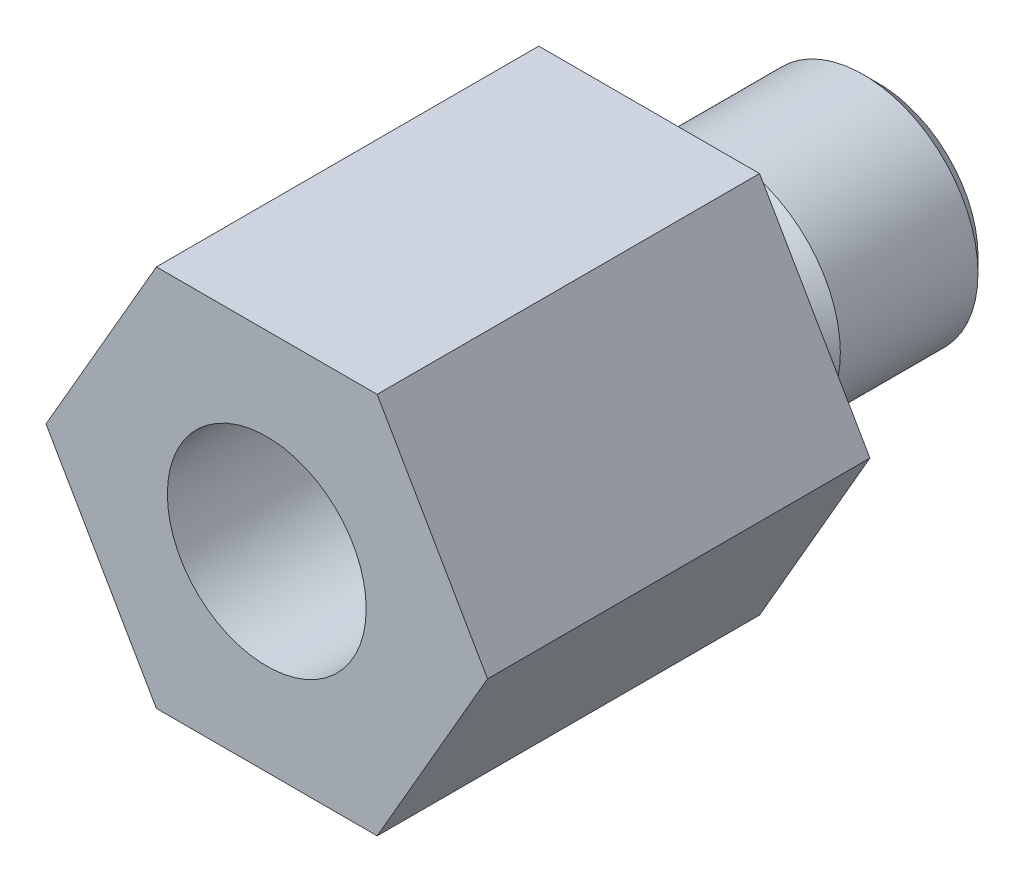
SolidWorks part; units mm, degrees
ref_plane "Plan de face" through (0, 0, 0) normal (0, 0, 1) x (1, 0, 0)
ref_plane "Plan de dessus" through (0, 0, 0) normal (0, 1, 0) x (1, 0, 0)
ref_plane "Plan de droite" through (0, 0, 0) normal (1, 0, 0) x (0, 0, -1)
sketch "Esquisse1" plane through (0, 0, 0) normal (0, 0, 1) x (1, 0, 0)
  line L1 (1.4434, 2.5) -> (-1.4434, 2.5)
  line L2 (-1.4434, 2.5) -> (-2.8868, 0)
  line L3 (-2.8868, 0) -> (-1.4434, -2.5)
  line L4 (-1.4434, -2.5) -> (1.4434, -2.5)
  line L5 (1.4434, -2.5) -> (2.8868, 0)
  line L6 (2.8868, 0) -> (1.4434, 2.5)
  circle A0 centre (0, 0) radius 2.5 construction
  dimension "D1" = 5
extrude "Extrusion1" add sketch "Esquisse1" along normal blind 5
sketch "Esquisse2" plane through (0, 0, 0) normal (0, 0, -1) x (-1, 0, 0)
  circle A0 centre (0, 0) radius 1.5
extrude "Extrusion2" add sketch "Esquisse2" along normal blind 3
cosmetic thread "Représentation de filetage1" parameters "D1"=3, "D2"=2.6
chamfer "Chanfrein1" distance 0.2 angle 45
sketch "Esquisse3" plane through (0, 0, 5) normal (0, 0, 1) x (1, 0, 0)
  circle A0 centre (0, 0) radius 1.3
extrude "Enlèv. mat.-Extru.1" cut sketch "Esquisse3" against normal blind 3
cosmetic thread "Représentation de filetage2" parameters "D1"=3, "D2"=3
sketch "Esquisse4" plane through (0, 0, 0) normal (0, 1, 0) x (1, 0, 0)
  line L0 (0, 4.3748) -> (0, -5.5215) construction
  line L1 (1.2, 0.6172) -> (1.2, 0.2)
  line L2 (1.8048, 0) -> (1.8048, 1.3048)
  line L3 (2.8868, 0) -> (1.4434, 0) construction
  line L5 (1.8048, 1.3048) -> (1.2586, 0.7586)
  line L7 (1.8048, 0) -> (1.4, 0)
  arc A0 (1.2586, 0.7586) -> (1.2, 0.6172) centre (1.4, 0.6172) ccw
  arc A1 (1.2, 0.2) -> (1.4, 0) centre (1.4, 0.2) ccw
  dimension "D2" = 0.2
  dimension "D3" = 0.2
  dimension "D1" = 1.2
revolve "Enlèvement de matière-Révolution1" cut sketch "Esquisse4" angle 360 about L0
